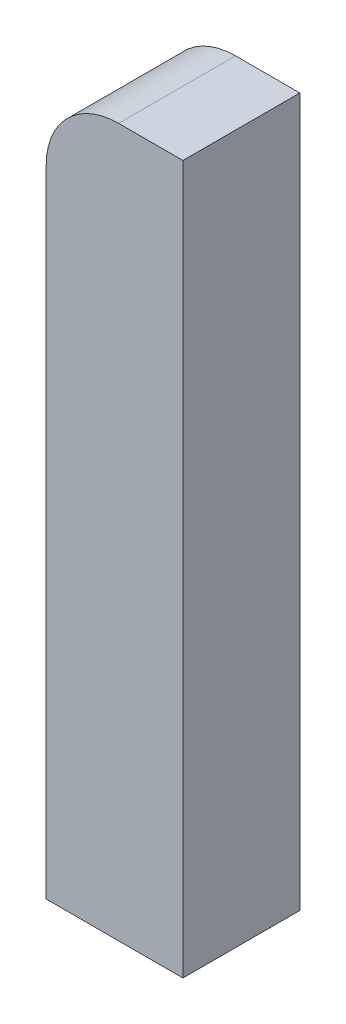
SolidWorks part; units mm, degrees
material "POLYURETHANE (11671)"
ref_plane "Front Plane" through (0, 0, 0) normal (0, 0, 1) x (1, 0, 0)
ref_plane "Top Plane" through (0, 0, 0) normal (0, 1, 0) x (1, 0, 0)
ref_plane "Right Plane" through (0, 0, 0) normal (1, 0, 0) x (0, 0, -1)
sketch "Sketch1" plane through (0, 0, 0) normal (0, 0, 1) x (1, 0, 0)
  line L0 (0, 0) -> (37.75, 0)
  line L1 (37.75, 0) -> (37.75, 29.178)
  line L2 (37.75, 29.178) -> (28.3125, 48.144)
  line L3 (28.3125, 48.144) -> (28.3125, 145.891)
  line L4 (28.3125, 145.891) -> (9.4375, 145.891)
  line L5 (9.4375, 145.891) -> (9.4375, 48.144)
  line L6 (9.4375, 48.144) -> (0, 29.178)
  line L7 (0, 29.178) -> (0, 0)
  line L8 (5.6625, 8.494) -> (32.0875, 8.494) construction
  circle A0 centre (5.6625, 8.494) radius 1.7
  circle A1 centre (32.0875, 8.494) radius 1.7
  point P13 (18.875, 8.494)
  point P14 (18.875, 0)
  dimension "D8" = 3.4
  dimension "D1" = 29.178
  dimension "D2" = 48.144
  dimension "D3" = 145.891
  dimension "D4" = 26.425
  dimension "D5" = 37.75
  dimension "D6" = 8.494
  dimension "D7" = 18.875
extrude "Boss-Extrude3" add sketch "Sketch1" along normal blind 16.141
sketch "Sketch2" plane through (0, 0, 16.141) normal (0, 0, 1) x (1, 0, 0)
  line L1 (9.4375, 48.144) -> (28.3125, 48.144)
  line L13 (0, 29.178) -> (0, 0)
  line L17 (0, 0) -> (37.75, 0)
  line L27 (37.75, 0) -> (37.75, 29.178)
  line L28 (37.75, 29.178) -> (28.3125, 48.144)
  line L29 (28.3125, 48.144) -> (28.3125, 145.891)
  line L30 (28.3125, 145.891) -> (9.4375, 145.891)
  line L31 (9.4375, 145.891) -> (9.4375, 48.144)
  line L32 (9.4375, 48.144) -> (0, 29.178)
  line L33 (0, 29.178) -> (0, 0)
  line L34 (0, 0) -> (37.75, 0)
  line L35 (37.75, 0) -> (37.75, 29.178)
  line L36 (37.75, 29.178) -> (28.3125, 48.144)
  line L40 (9.4375, 48.144) -> (0, 29.178)
  dimension "D1" = 0
extrude "Cut-Extrude1" cut sketch "Sketch2" against normal through all
fillet "Fillet1" radius 10 1 edges at (9.4375, 145.891, 8.0705)
equation "\"B1\"=0.037750"
equation "\"B2\"=0.018875"
equation "\"B3\"=0.055704"
equation "\"H1\"=0.029178"
equation "\"H2\"=0.048144"
equation "\"H3\"=0.126925"
equation "\"H4\"=0.145891"
equation "\"T\"=0.005000"
equation "\"L\"=0.026425"
equation "\"bolt_hole_diameter\"=0.003400"
equation "\"D1@Sketch1\"=\"H1\"*1000"
equation "\"D2@Sketch1\"=\"H2\"*1000"
equation "\"D3@Sketch1\"=\"H4\"*1000"
equation "\"D4@Sketch1\"=\"L\"*1000"
equation "\"D5@Sketch1\"=\"B1\"*1000"
equation "\"D6@Sketch1\"=\"H_holes\"*1000"
equation "\"D7@Sketch1\"=\"B2\"*1000"
equation "\"D8@Sketch1\"=\"bolt_hole_diameter\"*1000"
equation "\"D1@Boss-Extrude3\"=\"pad_t1\"*1000"
equation "\"spring_arm_hole_pos\"=0.010570"
equation "\"spring_arm_hole_max_diam\"=0.006000"
equation "\"spring_arm_hole_min_diam\"=0.003400"
equation "\"arm_hole_head_height\"=0.001650"
equation "\"H_holes\"=0.008494"
equation "\"D_strap\"=0.071845"
equation "\"clip_hole_D\"=0.003400"
equation "\"clip_hole_y1\"=0.007500"
equation "\"clip_hole_dist\"=0.015000"
equation "\"pad_t1\"=0.016141"
equation "\"pad_t2\"=0.000000"
equation "\"unpad_L1\"=0.067481"
